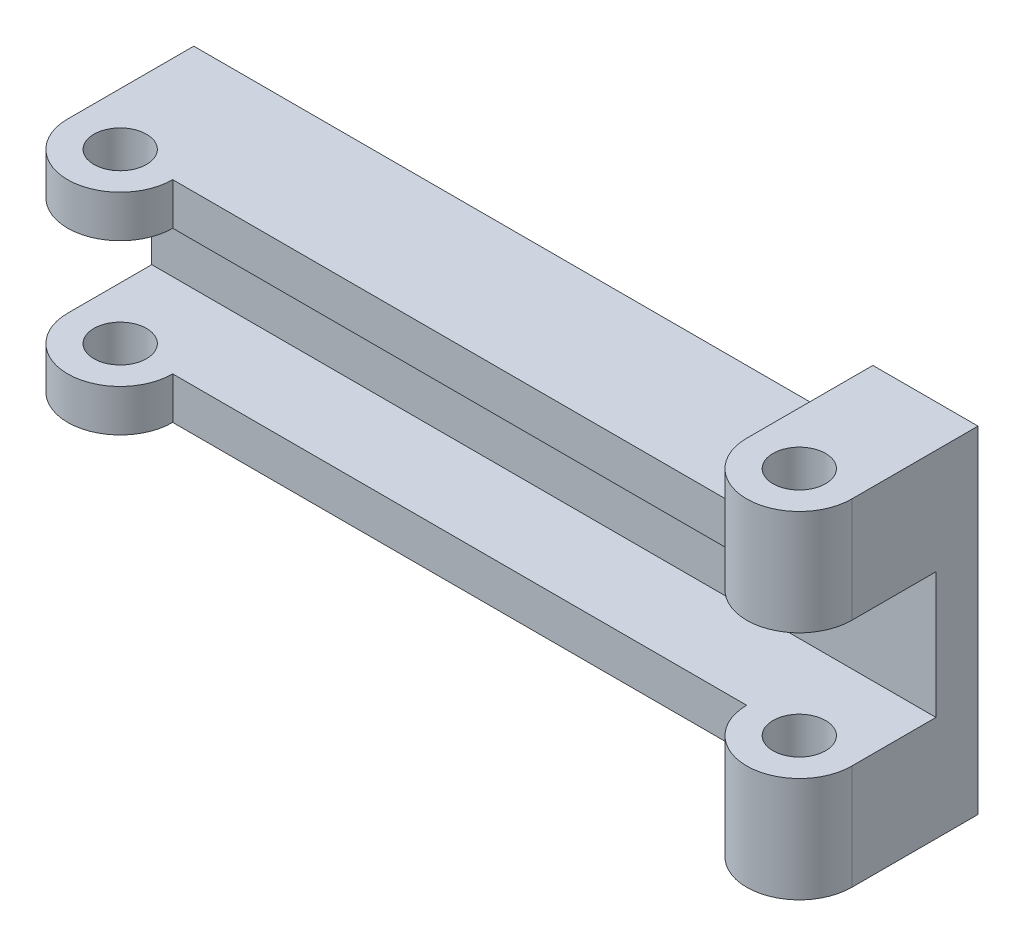
SolidWorks part; units mm, degrees
material "7075-T6 (SN)"
ref_plane "X-Y Datum" through (0, 0, 0) normal (0, 0, 1) x (1, 0, 0)
ref_plane "X-Z Datum" through (0, 0, 0) normal (0, 1, 0) x (1, 0, 0)
ref_plane "Y-Z Datum" through (0, 0, 0) normal (1, 0, 0) x (0, 0, -1)
sketch "Sketch2" plane through (0, 0, 0) normal (1, 0, 0) x (0, 0, -1)
  line L0 (0, -17.145) -> (0, 17.145)
  line L1 (0, 17.145) -> (-63.5, 17.145)
  line L2 (-63.5, 17.145) -> (-63.5, 9.525)
  line L3 (-63.5, 9.525) -> (-6.35, 9.525)
  line L4 (-6.35, 9.525) -> (-6.35, -9.525)
  line L6 (-6.35, 0) -> (0, 0) construction
  line L7 (0, -17.145) -> (-63.5, -17.145)
  line L8 (-63.5, -17.145) -> (-63.5, -9.525)
  line L9 (-63.5, -9.525) -> (-6.35, -9.525)
  dimension "D1" = 9.525
  dimension "D2" = 6.35
  dimension "D3" = 57.15
  dimension "D4" = 7.62
extrude "Boss-Extrude1" [suppressed] add sketch "Sketch2" along normal blind 118.4275
sketch "Sketch3" [suppressed] plane through (0, 0, 0) normal (0, 1, 0) x (1, 0, 0)
  line L0 (0, 0) -> (0, -63.5) construction
  line L1 (118.4275, -6.35) -> (0, -6.35) construction
  line L2 (15.875, -19.05) -> (102.5525, -19.05)
  line L5 (0, -63.5) -> (0, -19.05)
  line L7 (110.49, -19.05) -> (7.9375, -19.05) construction
  line L9 (118.4275, -63.5) -> (0, -63.5)
  line L10 (118.4275, -63.5) -> (118.4275, -19.05)
  line L12 (110.49, -19.05) -> (118.4275, -19.05) construction
  circle A0 centre (7.9375, -19.05) radius 3.9688
  circle A1 centre (110.49, -19.05) radius 3.9688
  circle A2 centre (7.9375, -52.3875) radius 15.0812 construction
  arc A3 (7.9375, -52.3875) -> (33.4755, -40.4789) centre (7.9375, -19.05) ccw construction
  circle A4 centre (33.4755, -40.4789) radius 15.0812 construction
  arc A5 (0, -19.05) -> (15.875, -19.05) centre (7.9375, -19.05) ccw
  arc A7 (102.5525, -19.05) -> (118.4275, -19.05) centre (110.49, -19.05) ccw
  dimension "D1" = 7.9375
  dimension "D2" = 7.9375
  dimension "D6" = 30.1625
  dimension "D10" = 7.9375
  dimension "D11" = 7.9375
  dimension "D4" = 7.9375
  dimension "D5" = 12.7
  dimension "D8" = 50
extrude "Cut-Extrude1" [suppressed] cut sketch "Sketch3" against normal up to surface and the other way up to surface
sketch "Sketch4" [suppressed] plane through (0, 0, 0) normal (0, 0, 1) x (1, 0, 0)
  line L0 (0, -17.145) -> (0, 17.145) construction
  line L1 (118.4275, 9.525) -> (118.4275, -9.525) construction
  circle A0 centre (19.05, 0) radius 4.7625
  circle A1 centre (99.3775, 0) radius 4.7625
  dimension "D1" = 9.525
  dimension "D2" = 19.05
  dimension "D3" = 19.05
extrude "Cut-Extrude2" [suppressed] cut sketch "Sketch4" along normal up to surface (6.35 mm away)
sketch "Sketch6" plane through (0, 0, 0) normal (0, 0, 1) x (1, 0, 0)
  line L0 (0, 0) -> (0, -15.875)
  line L1 (0, -15.875) -> (102.5525, -15.875)
  line L2 (102.5525, -15.875) -> (102.5525, -25.4)
  line L3 (102.5525, -25.4) -> (118.4275, -25.4)
  line L4 (118.4275, -25.4) -> (118.4275, 0)
  line L5 (118.4275, 0) -> (0, 0)
  point P4 (66.2867, -9.525)
  point P10 (102.5525, -15.875)
  point P11 (102.5525, -44.5783)
  dimension "D1" = 118.4275
  dimension "D2" = 15.875
  dimension "D4" = 15.875
  dimension "D5" = 25.4
extrude "Boss-Extrude4" add sketch "Sketch6" along normal blind 6.35 contours L5 L0 L1 L2 L3 L4
sketch "Sketch9" plane through (0, -25.4, 0) normal (0, -1, 0) x (1, 0, 0)
  line L0 (102.5525, 6.35) -> (102.5525, 19.05)
  line L1 (118.4275, 19.05) -> (118.4275, 6.35)
  line L2 (118.4275, 6.35) -> (102.5525, 6.35)
  arc A0 (102.5525, 19.05) -> (118.4275, 19.05) centre (110.49, 19.05) cw
  circle A1 centre (110.49, 19.05) radius 3.9687
  dimension "D1" = 7.9375
  dimension "D2" = 7.9375
  dimension "D3" = 12.7
extrude "Boss-Extrude5" add sketch "Sketch9" against normal blind 15.875
sketch "Sketch10" plane through (0, -15.875, 0) normal (0, -1, 0) x (1, 0, 0)
  line L0 (0, 6.35) -> (0, 19.05)
  line L1 (15.875, 19.05) -> (102.5525, 19.05)
  line L2 (102.5525, 19.05) -> (102.5525, 6.35)
  line L3 (102.5525, 6.35) -> (0, 6.35)
  arc A0 (0, 19.05) -> (15.875, 19.05) centre (7.9375, 19.05) cw
  circle A1 centre (7.9375, 19.05) radius 3.9688
  dimension "D1" = 7.9375
  dimension "D2" = 7.9375
  dimension "D3" = 12.7
extrude "Boss-Extrude6" add sketch "Sketch10" against normal blind 6.35
mirror "Mirror1" about plane through (118.4275, 0, 6.35) normal (0, -1, 0) of bodies 108
